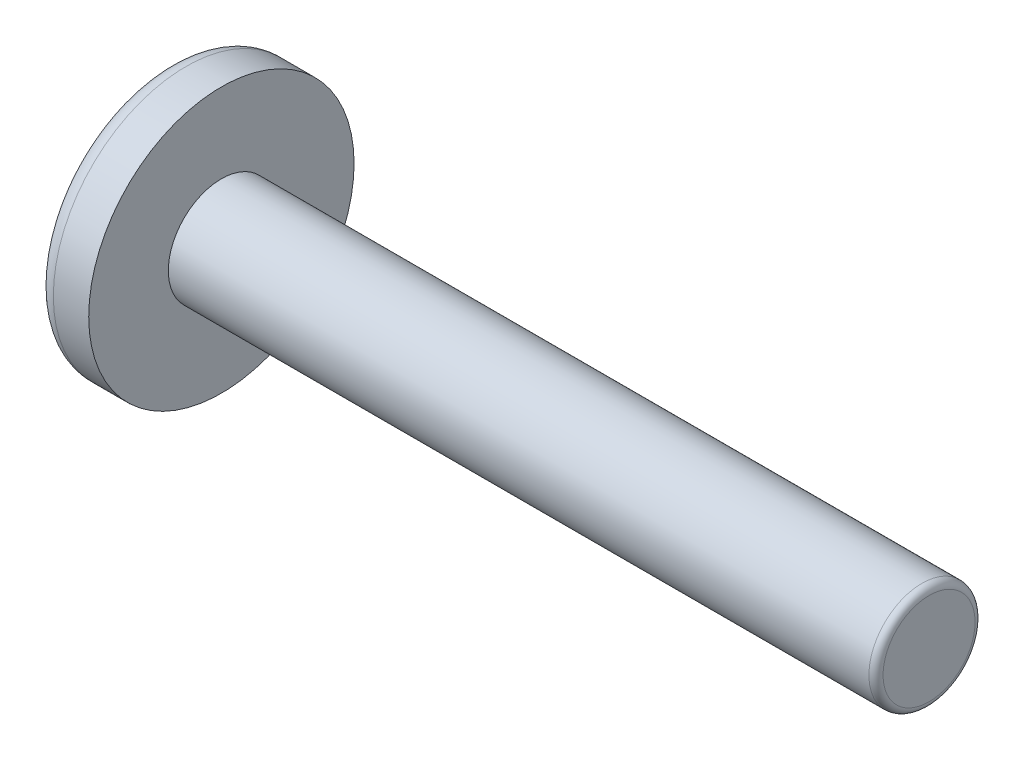
SolidWorks part; units mm, degrees
ref_plane "Front Plane" through (0, 0, 0) normal (0, 0, 1) x (1, 0, 0)
ref_plane "Top Plane" through (0, 0, 0) normal (0, 1, 0) x (1, 0, 0)
ref_plane "Right Plane" through (0, 0, 0) normal (1, 0, 0) x (0, 0, -1)
sketch "Sketch1" plane through (0, 0, 0) normal (1, 0, 0) x (0, 0, -1)
  circle A0 centre (0, 0) radius 1.5
  dimension "D1" = 3
extrude "Boss-Extrude1" add sketch "Sketch1" along normal blind 20
sketch "Sketch2" plane through (0, 0, 0) normal (-1, 0, 0) x (0, 0, 1)
  circle A0 centre (0, 0) radius 3.75
  dimension "D1" = 7.5
extrude "Boss-Extrude2" add sketch "Sketch2" along normal blind 1.5
fillet "Fillet1" radius 0.5 1 edges at (-1.5, 0, 3.75)
fillet "Fillet2" radius 0.2 1 edges at (20, 0, -1.5)
